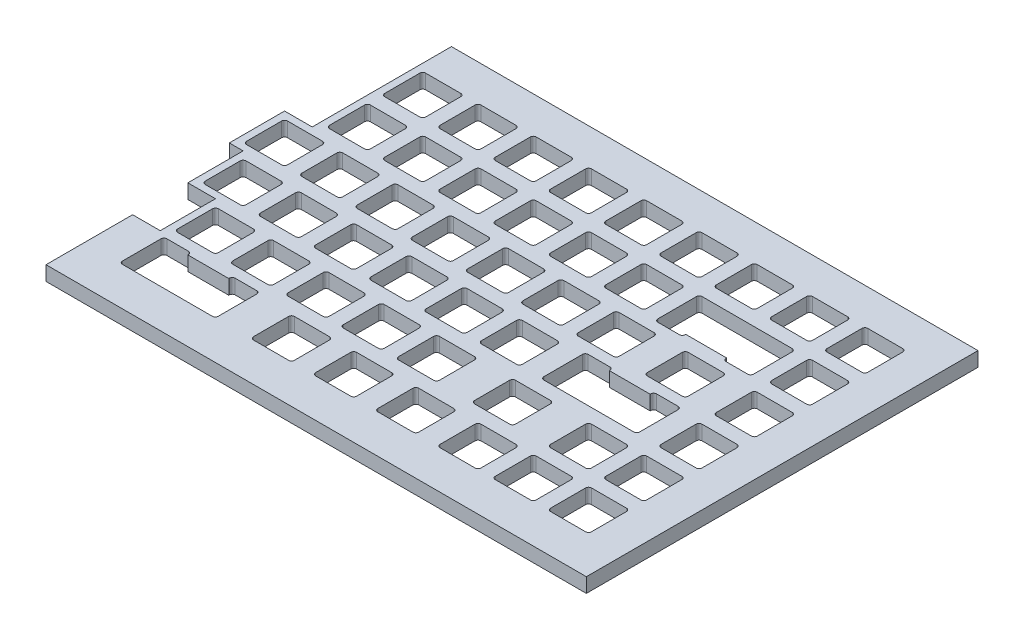
SolidWorks part; units mm, degrees
ref_plane "Front Plane" through (0, 0, 0) normal (0, 0, 1) x (1, 0, 0)
ref_plane "Top Plane" through (0, 0, 0) normal (0, 1, 0) x (1, 0, 0)
ref_plane "Right Plane" through (0, 0, 0) normal (1, 0, 0) x (0, 0, -1)
sketch "Sketch1" plane through (0, 0, 0) normal (0, 1, 0) x (1, 0, 0)
  line L0 (0, 0) -> (0, 135)
  line L1 (0, 135) -> (-181.5, 135)
  line L2 (-181.5, 135) -> (-181.5, 87)
  line L3 (-181.5, 87) -> (-191.025, 87)
  line L4 (-191.025, 87) -> (-191.025, 67.95)
  line L5 (-191.025, 67.95) -> (-186.2625, 67.95)
  line L6 (-186.2625, 67.95) -> (-186.2625, 48.9)
  line L7 (-186.2625, 48.9) -> (-176.7375, 48.9)
  line L8 (-176.7375, 48.9) -> (-176.7375, 29.85)
  line L9 (-176.7375, 29.85) -> (-186.2625, 29.85)
  line L10 (-186.2625, 29.85) -> (-186.2625, 0)
  line L11 (-186.2625, 0) -> (0, 0)
  dimension "D1" = 135
  dimension "D2" = 19.05
  dimension "D3" = 4.7625
  dimension "D4" = 9.525
  dimension "D6" = 181.5
  dimension "D7" = 9.525
  dimension "D5" = 48
extrude "Plate Frame" add sketch "Sketch1" along normal blind 5
sketch "Sketch2" plane through (0, 5, 0) normal (0, 1, 0) x (1, 0, 0)
  line L0 (-57.675, 20.325) -> (-38.625, 20.325) construction
  line L1 (-38.625, 20.325) -> (-19.575, 20.325) construction
  line L2 (-19.575, 20.325) -> (-19.575, 39.375) construction
  line L3 (-19.575, 39.375) -> (-19.575, 58.425) construction
  line L4 (-19.575, 58.425) -> (-19.575, 77.475) construction
  line L5 (-19.575, 77.475) -> (-19.575, 96.525) construction
  line L6 (-19.575, 96.525) -> (-19.575, 115.575) construction
  line L7 (-19.575, 115.575) -> (-38.625, 115.575) construction
  line L8 (-38.625, 115.575) -> (-57.675, 115.575) construction
  line L9 (-57.675, 115.575) -> (-76.725, 115.575) construction
  line L10 (-76.725, 115.575) -> (-95.775, 115.575) construction
  line L11 (-95.775, 115.575) -> (-114.825, 115.575) construction
  line L12 (-114.825, 115.575) -> (-133.875, 115.575) construction
  line L13 (-133.875, 115.575) -> (-152.925, 115.575) construction
  line L14 (-152.925, 115.575) -> (-171.975, 115.575) construction
  line L15 (-38.625, 39.375) -> (-19.575, 39.375) construction
  line L16 (-38.625, 39.375) -> (-38.625, 20.325) construction
  line L17 (-171.975, 96.525) -> (-152.925, 96.525) construction
  line L18 (-152.925, 96.525) -> (-133.875, 96.525) construction
  line L19 (-133.875, 96.525) -> (-114.825, 96.525) construction
  line L20 (-114.825, 96.525) -> (-95.775, 96.525) construction
  line L21 (-95.775, 96.525) -> (-76.725, 96.525) construction
  line L22 (-171.975, 96.525) -> (-171.975, 115.575) construction
  line L23 (-181.5, 135) -> (-181.5, 87) construction
  line L24 (-181.5, 77.475) -> (-162.45, 77.475) construction
  line L25 (-162.45, 77.475) -> (-143.4, 77.475) construction
  line L26 (-143.4, 77.475) -> (-124.35, 77.475) construction
  line L27 (-124.35, 77.475) -> (-105.3, 77.475) construction
  line L28 (-105.3, 77.475) -> (-86.25, 77.475) construction
  line L29 (-86.25, 77.475) -> (-67.2, 77.475) construction
  line L30 (-176.7375, 58.425) -> (-157.6875, 58.425) construction
  line L31 (-191.025, 87) -> (-191.025, 67.95) construction
  line L32 (-157.6875, 58.425) -> (-138.6375, 58.425) construction
  line L33 (-138.6375, 58.425) -> (-119.5875, 58.425) construction
  line L34 (-119.5875, 58.425) -> (-100.5375, 58.425) construction
  line L35 (-100.5375, 58.425) -> (-81.4875, 58.425) construction
  line L36 (-167.2125, 39.375) -> (-148.1625, 39.375) construction
  line L37 (-148.1625, 39.375) -> (-129.1125, 39.375) construction
  line L38 (-129.1125, 39.375) -> (-110.0625, 39.375) construction
  line L39 (-110.0625, 39.375) -> (-91.0125, 39.375) construction
  line L41 (-64.8187, 39.375) -> (-38.625, 39.375) construction
  line L42 (-57.675, 20.325) -> (-79.1062, 20.325) construction
  line L43 (-79.1062, 20.325) -> (-100.5375, 20.325) construction
  line L44 (-100.5375, 20.325) -> (-121.9688, 20.325) construction
  line L45 (-43.3875, 77.475) -> (-19.575, 77.475) construction
  point P0 (-19.575, 20.325)
  point P1 (-19.575, 39.375)
  point P2 (-19.575, 58.425)
  point P3 (-19.575, 77.475)
  point P4 (-19.575, 96.525)
  point P5 (-19.575, 115.575)
  point P6 (-38.625, 20.325)
  point P7 (-57.675, 20.325)
  point P8 (-38.625, 39.375)
  point P9 (-38.625, 115.575)
  point P10 (-57.675, 115.575)
  point P11 (-76.725, 115.575)
  point P12 (-95.775, 115.575)
  point P13 (-114.825, 115.575)
  point P14 (-133.875, 115.575)
  point P15 (-152.925, 115.575)
  point P16 (-171.975, 115.575)
  point P34 (-171.975, 96.525)
  point P35 (-152.925, 96.525)
  point P36 (-133.875, 96.525)
  point P37 (-114.825, 96.525)
  point P38 (-95.775, 96.525)
  point P39 (-76.725, 96.525)
  point P48 (-181.5, 77.475)
  point P49 (-162.45, 77.475)
  point P50 (-143.4, 77.475)
  point P51 (-124.35, 77.475)
  point P52 (-105.3, 77.475)
  point P53 (-86.25, 77.475)
  point P54 (-67.2, 77.475)
  point P62 (-157.6875, 58.425)
  point P65 (-191.025, 77.475)
  point P66 (-176.7375, 58.425)
  point P67 (-138.6375, 58.425)
  point P68 (-119.5875, 58.425)
  point P69 (-100.5375, 58.425)
  point P70 (-81.4875, 58.425)
  point P77 (-148.1625, 39.375)
  point P78 (-167.2125, 39.375)
  point P79 (-129.1125, 39.375)
  point P80 (-110.0625, 39.375)
  point P81 (-91.0125, 39.375)
  point P87 (-79.1062, 20.325)
  point P89 (-100.5375, 20.325)
  point P90 (-121.9688, 20.325)
  point P91 (-64.8187, 39.375)
  point P95 (-43.3875, 77.475)
  dimension "D1" = 19.05
  dimension "D2" = 9.525
  dimension "D3" = 9.525
  dimension "D4" = 4.7625
  dimension "D5" = 9.525
  dimension "D6" = 26.1938
  dimension "D7" = 21.4313
  dimension "D8" = 23.8125
sketch "Sketch3" plane through (0, 5, 0) normal (0, 1, 0) x (1, 0, 0)
  line L0 (-26.625, 14.275) -> (-26.625, 26.375)
  line L1 (-25.625, 27.375) -> (-13.525, 27.375)
  line L2 (-12.525, 26.375) -> (-12.525, 14.275)
  line L3 (-13.525, 13.275) -> (-25.625, 13.275)
  line L4 (-25.625, 27.375) -> (-13.525, 13.275) construction
  arc A0 (-26.625, 26.375) -> (-25.625, 27.375) centre (-25.625, 26.375) cw
  arc A1 (-13.525, 27.375) -> (-12.525, 26.375) centre (-13.525, 26.375) cw
  arc A2 (-12.525, 14.275) -> (-13.525, 13.275) centre (-13.525, 14.275) cw
  arc A3 (-25.625, 13.275) -> (-26.625, 14.275) centre (-25.625, 14.275) cw
  point P12 (-19.575, 20.325)
  point P13 (-58.0742, 32.292)
  point P14 (0, 0)
  dimension "D3" = 1
  dimension "D1" = 14.1
extrude "1U" cut sketch "Sketch3" against normal through all
pattern_sketch "Sketch-Pattern1" of "1U" driven by "Sketch2"
sketch "Sketch5" plane through (0, 5, 0) normal (0, 1, 0) x (1, 0, 0)
  line L0 (-19.575, 96.525) -> (-48.15, 96.525) construction
  line L1 (-19.575, 58.425) -> (-50.5312, 58.425) construction
  line L2 (-121.9688, 20.325) -> (-157.6875, 20.325) construction
  point P0 (-48.15, 96.525)
  point P1 (-50.5312, 58.425)
  point P2 (-157.6875, 20.325)
  point P12 (0, 0)
  dimension "D1" = 28.575
  dimension "D2" = 30.9563
  dimension "D3" = 35.7188
sketch "Sketch4" plane through (0, 5, 0) normal (0, 1, 0) x (1, 0, 0)
  line L0 (-64.65, 89.275) -> (-64.65, 102.575)
  line L1 (-63.65, 103.575) -> (-32.65, 103.575)
  line L2 (-31.65, 102.575) -> (-31.65, 89.275)
  line L3 (-32.65, 88.275) -> (-40.1, 88.275)
  line L5 (-56.2, 88.275) -> (-63.65, 88.275)
  line L6 (-55.2, 89.275) -> (-55.2, 89.475)
  line L7 (-55.2, 89.475) -> (-41.1, 89.475)
  line L8 (-41.1, 89.475) -> (-41.1, 89.275)
  line L9 (-55.2, 89.475) -> (-41.1, 103.575) construction
  arc A0 (-64.65, 102.575) -> (-63.65, 103.575) centre (-63.65, 102.575) cw
  arc A1 (-32.65, 103.575) -> (-31.65, 102.575) centre (-32.65, 102.575) cw
  arc A2 (-31.65, 89.275) -> (-32.65, 88.275) centre (-32.65, 89.275) cw
  arc A3 (-40.1, 88.275) -> (-41.1, 89.275) centre (-40.1, 89.275) cw
  arc A4 (-55.2, 89.275) -> (-56.2, 88.275) centre (-56.2, 89.275) cw
  arc A5 (-63.65, 88.275) -> (-64.65, 89.275) centre (-63.65, 89.275) cw
  point P18 (-128.8129, 57.5964)
  point P23 (-48.15, 96.525)
  dimension "D1" = 1
  dimension "D2" = 14.1
  dimension "D3" = 33
  dimension "D4" = 14.1
  dimension "D5" = 15.3
sketch "Sketch6" plane through (0, 5, 0) normal (0, 1, 0) x (1, 0, 0)
  line L9 (-173.1875, 13.275) -> (-142.1875, 13.275)
  line L10 (-66.0312, 51.375) -> (-35.0312, 51.375)
  line L11 (-34.0312, 52.375) -> (-34.0312, 65.675)
  line L12 (-35.0312, 66.675) -> (-42.4812, 66.675)
  line L13 (-43.4812, 65.675) -> (-43.4812, 65.475)
  line L14 (-43.4812, 65.475) -> (-57.5812, 65.475)
  line L15 (-57.5812, 65.475) -> (-57.5812, 65.675)
  line L16 (-58.5812, 66.675) -> (-66.0312, 66.675)
  line L17 (-67.0312, 65.675) -> (-67.0312, 52.375)
  line L18 (-43.4812, 65.475) -> (-57.5812, 51.375) construction
  line L19 (-141.1875, 14.275) -> (-141.1875, 27.575)
  line L20 (-142.1875, 28.575) -> (-149.6375, 28.575)
  line L21 (-150.6375, 27.575) -> (-150.6375, 27.375)
  line L22 (-150.6375, 27.375) -> (-164.7375, 27.375)
  line L23 (-164.7375, 27.375) -> (-164.7375, 27.575)
  line L24 (-165.7375, 28.575) -> (-173.1875, 28.575)
  line L25 (-174.1875, 27.575) -> (-174.1875, 14.275)
  line L26 (-150.6375, 27.375) -> (-164.7375, 13.275) construction
  arc A6 (-35.0312, 51.375) -> (-34.0312, 52.375) centre (-35.0312, 52.375) ccw
  arc A7 (-34.0312, 65.675) -> (-35.0312, 66.675) centre (-35.0312, 65.675) ccw
  arc A8 (-42.4812, 66.675) -> (-43.4812, 65.675) centre (-42.4812, 65.675) ccw
  arc A10 (-66.0312, 66.675) -> (-67.0312, 65.675) centre (-66.0312, 65.675) ccw
  arc A11 (-67.0312, 52.375) -> (-66.0312, 51.375) centre (-66.0312, 52.375) ccw
  arc A12 (-58.5812, 66.675) -> (-57.5812, 65.675) centre (-58.5812, 65.675) cw
  arc A13 (-142.1875, 13.275) -> (-141.1875, 14.275) centre (-142.1875, 14.275) ccw
  arc A14 (-141.1875, 27.575) -> (-142.1875, 28.575) centre (-142.1875, 27.575) ccw
  arc A15 (-149.6375, 28.575) -> (-150.6375, 27.575) centre (-149.6375, 27.575) ccw
  arc A16 (-173.1875, 28.575) -> (-174.1875, 27.575) centre (-173.1875, 27.575) ccw
  arc A17 (-174.1875, 14.275) -> (-173.1875, 13.275) centre (-173.1875, 14.275) ccw
  arc A18 (-165.7375, 28.575) -> (-164.7375, 27.575) centre (-165.7375, 27.575) cw
  point P0 (23.4016, 55.9514)
  point P21 (-157.6875, 20.325)
  point P34 (-41.8406, 52.9104)
  point P43 (-50.5312, 58.425)
  point P46 (7.0696, 58.9604)
  dimension "D6" = 1
  dimension "D2" = 1
  dimension "D3" = 14.1
  dimension "D4" = 15.3
  dimension "D5" = 33
  dimension "D7" = 14.1
  dimension "D8" = 15.3
  dimension "D9" = 33
  dimension "D10" = 14.1
  dimension "D11" = 14.1
extrude "Cut-Extrude2" cut sketch "Sketch4" against normal through all
extrude "Cut-Extrude3" cut sketch "Sketch6" against normal through all
equation "\"D3@Sketch1\"=19.05/4"
equation "\"D2@Sketch2\"=19.05/2"
equation "\"D3@Sketch2\"=19.05/2"
equation "\"D4@Sketch2\"=19.05/4"
equation "\"D4@Sketch1\"=19.05/2"
equation "\"D5@Sketch2\"=19.05/2"
equation "\"D6@Sketch2\"=19.05 + 19.05*.75/2"
equation "\"D7@Sketch2\"=19.05/2 + 19.05*1.25/2"
equation "\"D8@Sketch2\"=19.05/2 + 19.05*1.5/2"
equation "\"D1@Sketch5\"=19.05*2/2 + 19.05/2"
equation "\"D2@Sketch5\"=19.05*2.25/2 + 19.05/2"
equation "\"D3@Sketch5\"=19.05*2.75/2 + 19.05/2"
